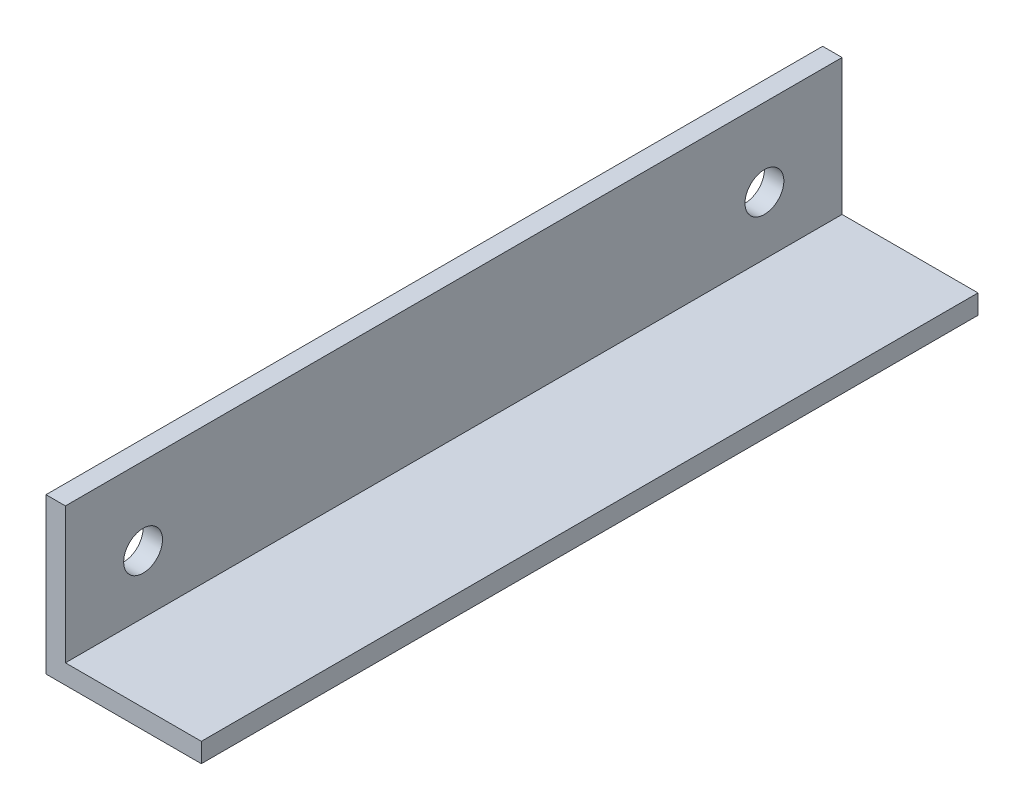
SolidWorks part; units mm, degrees
ref_plane "Front Plane" through (0, 0, 0) normal (0, 0, 1) x (1, 0, 0)
ref_plane "Top Plane" through (0, 0, 0) normal (0, 1, 0) x (1, 0, 0)
ref_plane "Right Plane" through (0, 0, 0) normal (1, 0, 0) x (0, 0, -1)
sketch "Sketch1" plane through (0, 0, 0) normal (0, 0, 1) x (1, 0, 0)
  line L0 (6.5009, 0) -> (-18.8991, 0)
  line L1 (-18.8991, 0) -> (-18.8991, 25.4)
  line L2 (-18.8991, 25.4) -> (-15.7241, 25.4)
  line L3 (-15.7241, 25.4) -> (-15.7241, 3.175)
  line L4 (-15.7241, 3.175) -> (6.5009, 3.175)
  line L5 (6.5009, 3.175) -> (6.5009, 0)
  dimension "D1" = 25.4
  dimension "D2" = 3.175
extrude "Boss-Extrude1" add sketch "Sketch1" along normal mid plane 127
sketch "Sketch2" plane through (-18.8991, 0, 0) normal (-1, 0, 0) x (0, 0, 1)
  line L0 (-63.5, 12.7) -> (63.5, 12.7) construction
  line L1 (-63.5, 25.4) -> (-63.5, 0) construction
  line L2 (63.5, 25.4) -> (63.5, 0) construction
  line L3 (0, 12.7) -> (0, 38.0231) construction
  circle A0 centre (50.8, 12.7) radius 3.175
  circle A1 centre (-50.8, 12.7) radius 3.175
  dimension "D1" = 6.35
  dimension "D2" = 12.7
extrude "Cut-Extrude1" cut sketch "Sketch2" against normal blind 127
